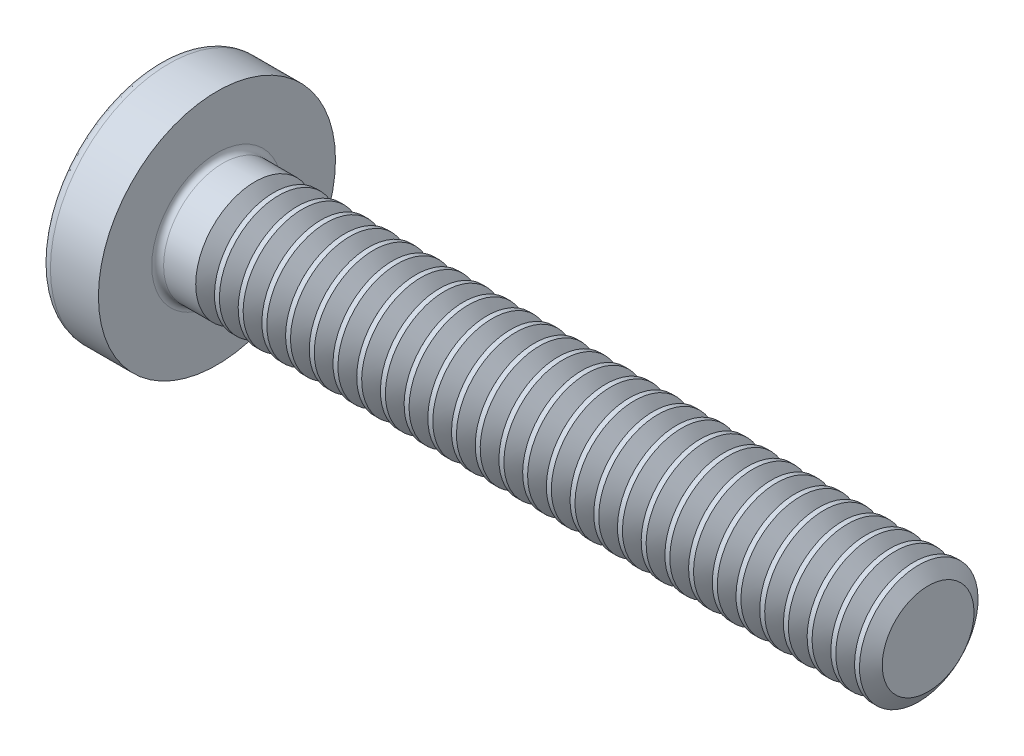
SolidWorks part; units mm, degrees
ref_plane "Plane1" through (0, 0, 0) normal (0, 0, 1) x (1, 0, 0)
ref_plane "Plane2" through (0, 0, 0) normal (0, 1, 0) x (1, 0, 0)
ref_plane "Plane3" through (0, 0, 0) normal (1, 0, 0) x (0, 0, -1)
sketch "BodySke" plane through (0, 0, 0) normal (0, 0, 1) x (1, 0, 0)
  line L0 (1.6, 1) -> (1.6, 2)
  line L1 (1.8, 6.35) -> (1.8, -3.175) construction
  line L2 (-25.4, 0) -> (127, 0) construction
  line L3 (13.6, 0) -> (0, 0)
  line L4 (1.6, 1) -> (13.6, 1)
  line L5 (13.6, 1) -> (13.6, 0)
  line L6 (0.79, 2) -> (1.6, 2)
  line L8 (1.6, 6.35) -> (1.6, -3.175) construction
  arc A0 (0.6464, 1.9285) -> (0, 0) centre (3.2, 0) ccw
  arc A2 (0.6464, 1.9285) -> (0.79, 2) centre (0.79, 1.82) cw
  dimension "Head_crown_rad" = 3.2
  dimension "Head_fillet_rad" = 0.18
  dimension "Length" = 12
  dimension "Head_ht" = 1.6
  dimension "Head_dia" = 4
  dimension "Advance" = 0.4
  dimension "Thread_nom" = 12
  dimension "Diameter" = 2
revolve "Base-Revolve" add sketch "BodySke"
cosmetic thread "ThreadCosmetic" [suppressed]
fillet "Fillet1" radius 0.1 1 edges at (1.6, 0, 1)
sketch "Sketch3" plane through (0, 0, 0) normal (1, 0, 0) x (0, 0, -1)
  line L0 (0.24, -1.05) -> (-0.24, -1.05)
  line L1 (0.24, -1.05) -> (0.24, 1.05)
  line L2 (-0.24, 1.05) -> (0.24, 1.05)
  line L3 (-0.24, 1.05) -> (-0.24, -1.05)
  dimension "Cross_dia" = 2.1
  dimension "D1" = 1.05
  dimension "Cross_width" = 0.48
  dimension "D2" = 0.24
ref_plane "Plane4" through (1.42, 0, 0) normal (1, 0, 0) x (0, 0, -1)
sketch "Sketch4" plane through (1.42, 0, 0) normal (1, 0, 0) x (0, 0, -1)
  line L0 (0.24, -0.342) -> (-0.24, -0.342)
  line L1 (0.24, -0.342) -> (0.24, 0.342)
  line L2 (-0.24, 0.342) -> (0.24, 0.342)
  line L3 (-0.24, 0.342) -> (-0.24, -0.342)
  dimension "D1" = 0.48
  dimension "D2" = 0.684
  dimension "D3" = 0.24
  dimension "D4" = 0.342
loft "Recess" cut profiles "Sketch3", "Sketch4"
pattern_circular "RecPat" count 2 every 90 about axis through (0, 0, 0) along (1, 0, 0) of "Recess"
sketch "RecCorSke" plane through (0, 0, 0) normal (0, 0, 1) x (1, 0, 0)
  line L0 (-3.175, 0) -> (15.875, 0) construction
  line L1 (-25.4, 0) -> (127, 0) construction
  line L2 (0, 0) -> (0, 0.4548)
  line L3 (0, 0.4548) -> (1.42, 0.3555)
  line L4 (1.42, 0.3555) -> (1.5355, 0)
  line L5 (1.5355, 0) -> (0, 0)
  dimension "Diameter" = 0.711
  dimension "Depth" = 1.42
  dimension "Draft_angle" = 4
  dimension "Bottom_angle" = 18
revolve "RecessCore" cut sketch "RecCorSke" angle 360 about L0
sketch "ThdSchSke" plane through (0, 0, 0) normal (0, 0, 1) x (1, 0, 0)
  line L0 (2.4, -0.774) -> (2.2418, -1)
  line L1 (2.4, -0.774) -> (2.5582, -1)
  line L2 (2.5582, -1) -> (2.5582, -1.25)
  line L3 (-3.175, 0) -> (5.1513, 0) construction
  line L5 (2.5582, -1.25) -> (2.2418, -1.25)
  line L6 (2.2418, -1.25) -> (2.2418, -1)
  dimension "Diameter" = 2
  dimension "SideAngle" = 55
  dimension "VeeAngle" = 70
  dimension "Thread_minor" = 1.548
  dimension "Overcut" = 2.5
  dimension "Start" = 2.4
revolve "ThreadSchematic" cut sketch "ThdSchSke" angle 360 about L3
pattern_linear "ThdSchPat" count 29 spacing 0.4 along (1, 0, 0) of "ThreadSchematic"
equation "\"D1@Sketch3\" = \"Cross_dia@Sketch3\" / 2"
equation "\"D2@Sketch3\" = \"Cross_width@Sketch3\" / 2"
equation "\"Depth@RecCorSke\" = \"Cross_depth@Plane4\""
equation "\"D1@Sketch4\" = \"Cross_width@Sketch3\""
equation "\"D2@Sketch4\" = \"Cross_dia@Sketch3\" - 2.0 * \"Cross_depth@Plane4\" * tan(26.5  * 0.017453292)"
equation "\"D3@Sketch4\" = \"D1@Sketch4\" / 2"
equation "\"D4@Sketch4\" = \"D2@Sketch4\" / 2"
equation "\"Thread_length@ThreadCosmetic\" = ((sgn( (\"Length@BodySke\" - \"Advance@BodySke\" * 2.0 ) - \"Thread_nom@BodySke\" )-1)*( (\"Length@BodySke\" - \"Advance@BodySke\" * 2.0 ) - \"Thread_nom@BodySke\" ))/-2+ \"Thread_nom@BodySke\""
equation "\"Thread_minor@ThdSchSke\" = \"Thread_minor@ThreadCosmetic\""
equation "\"Diameter@ThdSchSke\" = \"Diameter@BodySke\""
equation "\"Overcut@ThdSchSke\" = \"Diameter@BodySke\" * 1.25"
equation "\"Start@ThdSchSke\" = \"Head_ht@BodySke\" + \"Length@BodySke\" - \"Thread_length@ThreadCosmetic\"  '---Non-countersunk---"
equation "\"Num_threads@ThdSchPat\" = int( \"Thread_length@ThreadCosmetic\" / \"Advance@BodySke\" + 0.999 )  + 1"
equation "\"Advance@ThdSchPat\" = \"Thread_length@ThreadCosmetic\" /  (\"Num_threads@ThdSchPat\" - 1) 'relax it"
